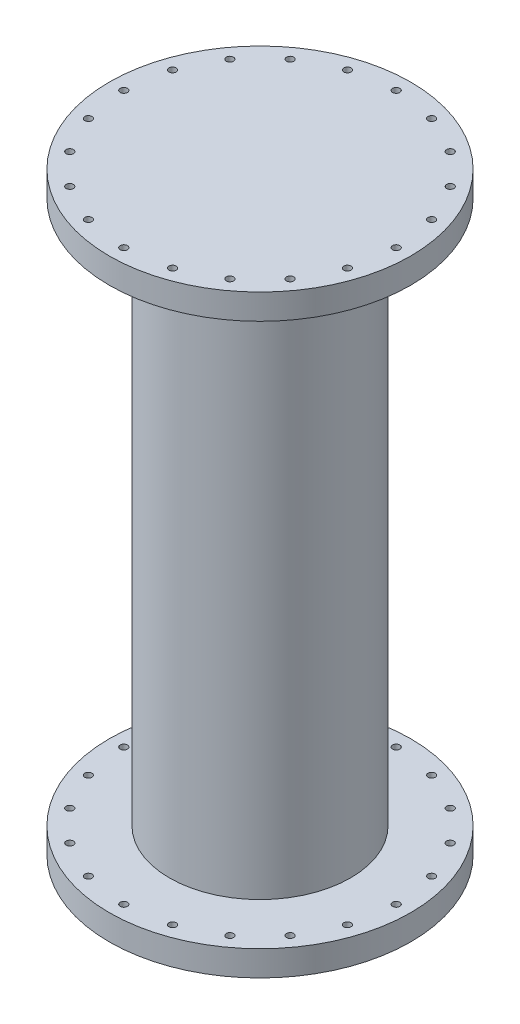
SolidWorks part; units mm, degrees
ref_plane "Plan de face" through (0, 0, 0) normal (0, 0, 1) x (1, 0, 0)
ref_plane "Plan de dessus" through (0, 0, 0) normal (0, 1, 0) x (1, 0, 0)
ref_plane "Plan de droite" through (0, 0, 0) normal (1, 0, 0) x (0, 0, -1)
sketch "Esquisse1" plane through (0, 0, 0) normal (0, 0, 1) x (1, 0, 0)
  line L0 (0, 0) -> (0, -1756.5308) construction
  line L1 (0, 0) -> (416, 0)
  line L2 (0, 0) -> (0, -70)
  line L3 (0, -70) -> (200, -70)
  line L4 (416, 0) -> (416, -70)
  line L26 (250, -70) -> (416, -70)
  line L27 (250, -1570) -> (416, -1570)
  line L29 (200, -70) -> (200, -1570)
  line L31 (250, -70) -> (250, -1570)
  line L32 (0, -1570) -> (200, -1570)
  line L33 (0, -1570) -> (0, -1640)
  line L34 (0, -1640) -> (416, -1640)
  line L35 (416, -1570) -> (416, -1640)
  dimension "D1" = 416
  dimension "D2" = 70
  dimension "D3" = 70
  dimension "D4" = 416
  dimension "D5" = 250
  dimension "D6" = 200
  dimension "D7" = 1500
revolve "Révolution1" add sketch "Esquisse1" angle 360 about L0
sketch "Esquisse2" plane through (0, 0, 0) normal (0, 1, 0) x (1, 0, 0)
  circle A0 centre (376, 0) radius 10
  dimension "D2" = 20
  dimension "D1" = 376
extrude "Enlèv. mat.-Extru.1" cut sketch "Esquisse2" against normal through all
pattern_circular "Répétition circulaire1" count 20 over 360 about axis through (0, 0, 0) along (0, 1, 0) of "Enlèv. mat.-Extru.1"
sketch "Esquisse3" plane through (0, -1640, 0) normal (0, -1, 0) x (-1, 0, 0)
  circle A0 centre (0, 0) radius 416
  point P4 (0, 0)
